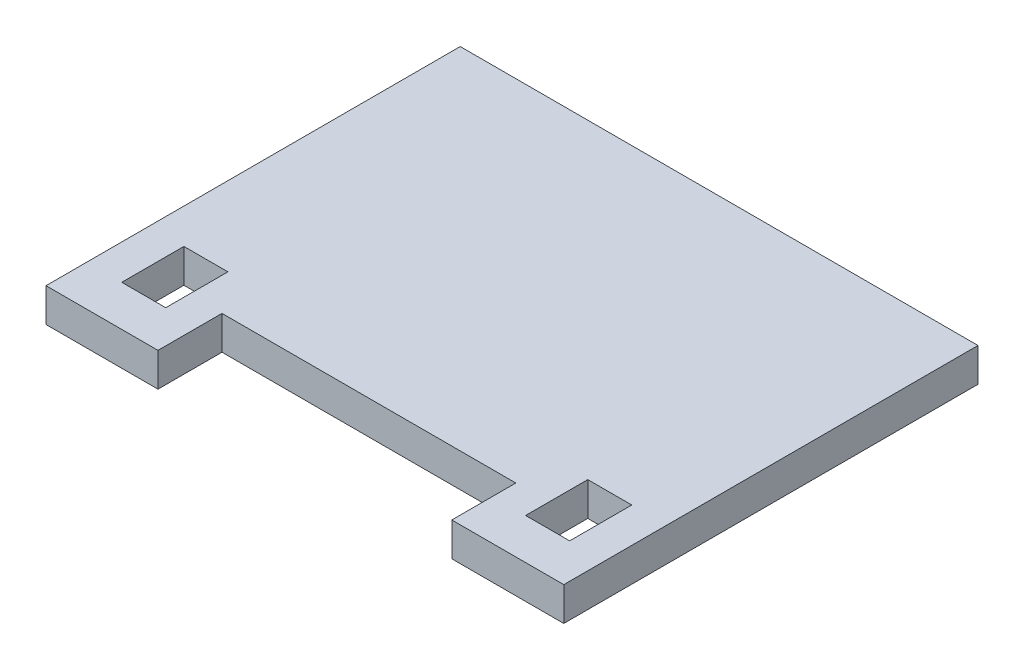
SolidWorks part; units mm, degrees
ref_plane "Front Plane" through (0, 0, 0) normal (0, 0, 1) x (1, 0, 0)
ref_plane "Top Plane" through (0, 0, 0) normal (0, 1, 0) x (1, 0, 0)
ref_plane "Right Plane" through (0, 0, 0) normal (1, 0, 0) x (0, 0, -1)
sketch "Sketch1" plane through (0, 0, 0) normal (0, 1, 0) x (1, 0, 0)
  line L0 (6.75, 7.881) -> (15.25, 7.881)
  line L1 (0, 0) -> (100, 0)
  line L2 (0, 0) -> (0, 80)
  line L3 (0, 80) -> (100, 80)
  line L4 (100, 0) -> (100, 80)
  line L5 (84.75, 7.881) -> (93.25, 7.881)
  line L6 (84.75, 7.881) -> (84.75, 19.881)
  line L7 (84.75, 19.881) -> (93.25, 19.881)
  line L8 (93.25, 7.881) -> (93.25, 19.881)
  line L9 (6.75, 7.881) -> (6.75, 19.881)
  line L10 (6.75, 19.881) -> (15.25, 19.881)
  line L11 (15.25, 7.881) -> (15.25, 19.881)
  line L12 (15.25, 13.881) -> (84.75, 13.881) construction
  line L13 (50, 13.881) -> (50, 80) construction
  line L14 (50, 12.3625) -> (50, 80) construction
  line L15 (21.6283, 0) -> (78.3717, 0)
  line L16 (21.6283, 0) -> (21.6283, 12.3625)
  line L17 (21.6283, 12.3625) -> (78.3717, 12.3625)
  line L18 (78.3717, 0) -> (78.3717, 12.3625)
  point P22 (50, 12.3625)
  dimension "D1" = 100
  dimension "D2" = 80
  dimension "D3" = 12
  dimension "D4" = 8.5
  dimension "D5" = 90
  dimension "D6" = 69.5
  dimension "D7" = 12
  dimension "D8" = 8.5
  dimension "D9" = 90
  dimension "D10" = 90
extrude "Boss-Extrude1" add sketch "Sketch1" along normal blind 6.5 contours L18 L1 L4 L3 L2 L16 L17 L11 L0 L9 L10 L8 L5 L6 L7
